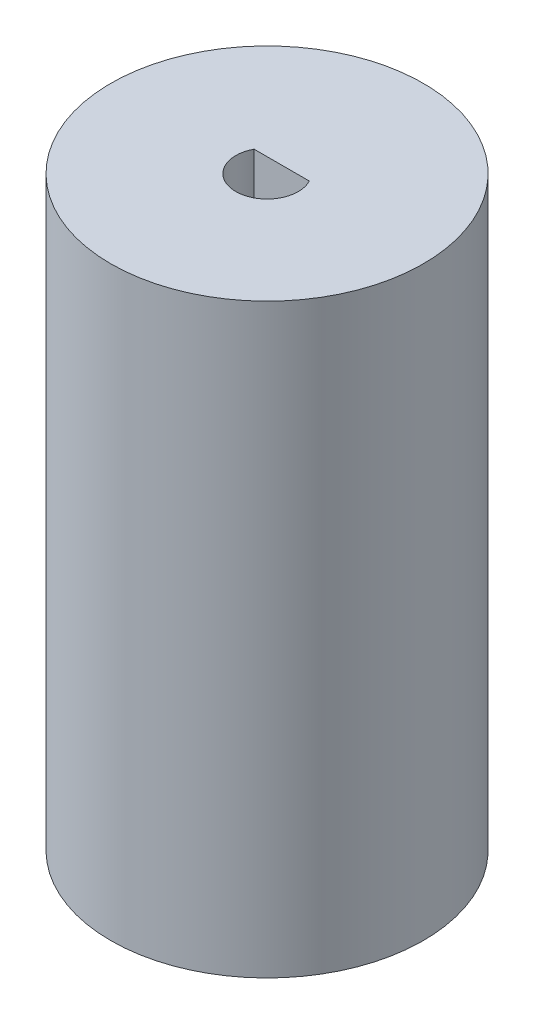
SolidWorks part; units mm, degrees
ref_plane "Front Plane" through (0, 0, 0) normal (0, 0, 1) x (1, 0, 0)
ref_plane "Top Plane" through (0, 0, 0) normal (0, 1, 0) x (1, 0, 0)
ref_plane "Right Plane" through (0, 0, 0) normal (1, 0, 0) x (0, 0, -1)
sketch "Sketch1" plane through (0, 0, 0) normal (0, 1, 0) x (1, 0, 0)
  line L0 (0, 0) -> (0, 0.75) construction
  line L1 (-1.4133, 0.75) -> (1.4133, 0.75)
  circle A0 centre (0, 0) radius 8
  circle A1 centre (0, 0) radius 1.6
  dimension "D1" = 16
  dimension "D2" = 3.2
  dimension "D3" = 0.75
extrude "Boss-Extrude1" add sketch "Sketch1" along normal blind 30 contours L1 A1 | A0 A1
